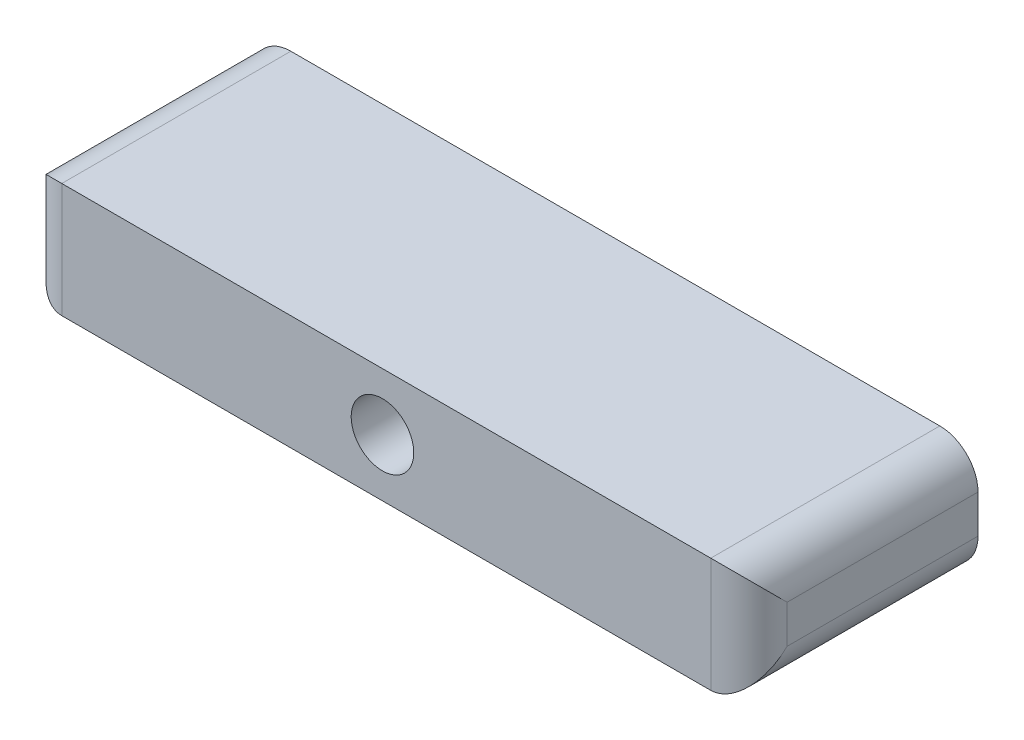
SolidWorks part; units mm, degrees
ref_plane "Front Plane" through (0, 0, 0) normal (0, 0, 1) x (1, 0, 0)
ref_plane "Top Plane" through (0, 0, 0) normal (0, 1, 0) x (1, 0, 0)
ref_plane "Right Plane" through (0, 0, 0) normal (1, 0, 0) x (0, 0, -1)
sketch "Esquisse1" plane through (0, 0, 0) normal (0, 1, 0) x (1, 0, 0)
  line L1 (0, 0) -> (-95, 0)
  line L2 (0, 0) -> (0, -30)
  line L3 (0, -30) -> (-95, -30)
  line L4 (-95, 0) -> (-95, -30)
  dimension "D1" = 95
  dimension "D2" = 30
extrude "Boss.-Extru.1" add sketch "Esquisse1" along normal blind 15
sketch "Esquisse2" plane through (0, 0, 0) normal (0, 0, -1) x (-1, 0, 0)
  line L0 (0, 15) -> (0, 0) construction
  line L3 (0, 0) -> (95, 0) construction
  circle A0 centre (10, 7) radius 4.25
  circle A1 centre (85, 7) radius 4.25
  point P6 (0, 0)
  point P9 (0, 0)
  dimension "D2" = 8.5
  dimension "D3" = 8.5
  dimension "D1" = 75
  dimension "D4" = 10
  dimension "D6" = 7
extrude "Enlèv. mat.-Extru.2" cut sketch "Esquisse2" against normal blind 20
sketch "Esquisse3" plane through (0, 0, 0) normal (0, 0, -1) x (-1, 0, 0)
  line L0 (0, 15) -> (95, 15) construction
  line L1 (0, 0) -> (95, 0) construction
  circle A0 centre (48, 7.5) radius 4.1
  circle A1 centre (10, 7) radius 4.25 construction
  dimension "D1" = 38
  dimension "D2" = 8.2
  dimension "D3" = 7.5
  dimension "D4" = 7.5
extrude "Enlèv. mat.-Extru.3" cut sketch "Esquisse3" against normal up to next
fillet "Congé1" radius 5 6 edges at (-95, 0, 15) (-95, 15, 15) (0, 0, 15) (0, 15, 15) (-95, 7.5, 30) (0, 7.5, 30)
